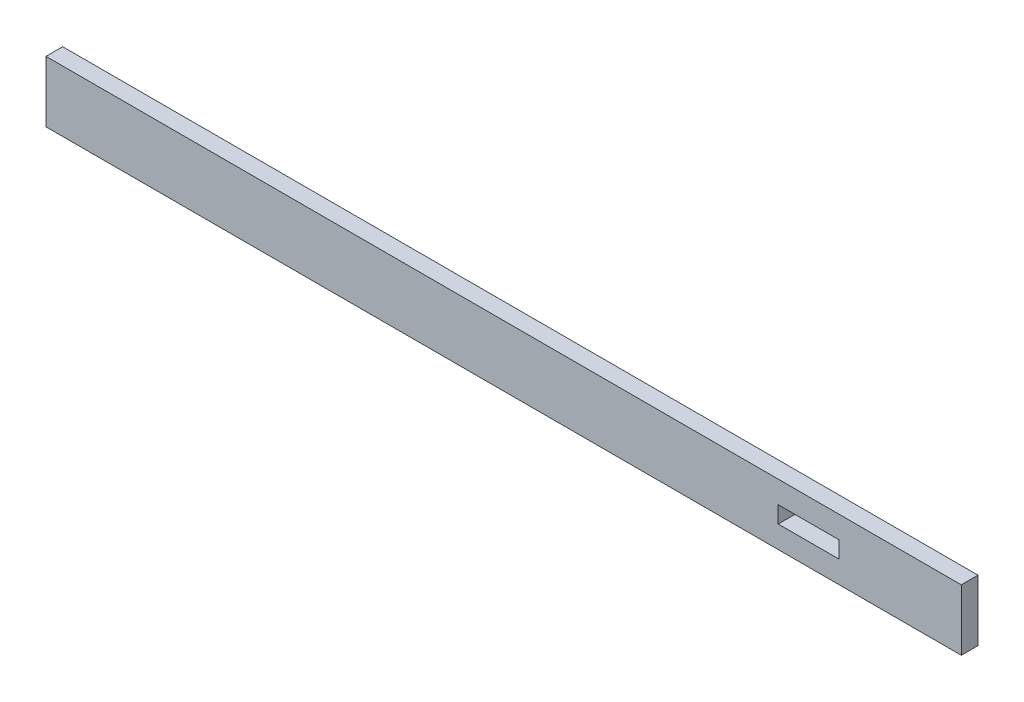
SolidWorks part; units mm, degrees
ref_plane "Front Plane" through (0, 0, 0) normal (1, 0, 0) x (0, 1, 0)
ref_plane "Top Plane" through (0, 0, 0) normal (0, 0, 1) x (0, 1, 0)
ref_plane "Right Plane" through (0, 0, 0) normal (0, 1, 0) x (-1, 0, 0)
sketch "Sketch1" plane through (0, 0, 0) normal (0, 0, 1) x (0, 1, 0)
  line L0 (5, 150) -> (5, 0) construction
  line L1 (0, 0) -> (10, 0)
  line L2 (0, 0) -> (0, 150)
  line L3 (0, 150) -> (10, 150)
  line L4 (10, 0) -> (10, 150)
  line L6 (3.63, 30) -> (6.37, 30)
  line L7 (3.63, 30) -> (3.63, 20)
  line L8 (3.63, 20) -> (6.37, 20)
  line L9 (6.37, 30) -> (6.37, 20)
  line L10 (3.63, 30) -> (6.37, 20) construction
  line L11 (3.63, 20) -> (6.37, 30) construction
  point P7 (5, 25)
  dimension "D1" = 150
  dimension "D2" = 10
  dimension "D3" = 2.74
  dimension "D4" = 10
  dimension "D5" = 20
extrude "Boss-Extrude1" add sketch "Sketch1" along normal blind 2.74
equation "\"cable width\"= .2in"
equation "\"clearance\"= 0.2mm"
equation "\"slot_width\"= \"cable width\" + \"clearance\""
equation "\"base\"= ( \"slot_width\" ) * 3 + 4 * ( 6 )"
equation "\"depth\" = 40mm"
equation "\"thick\"= 3mm"
equation "\"avg_t_wood\"= 2.74mm"
equation "\"ideal_t_wood\"= 3mm"
equation "\"kerf\"= 0.2mm"
equation "\"slot_height\"= \"avg_t_wood\" + \"kerf\""
equation "\"wood_slot_width\"= 10mm + \"kerf\""
equation "\"wood_slot_clearance\"= - .2mm"
equation "\"woodstand_width\"= 10mm"
equation "\"woodstand_length\" = 150mm"
equation "\"D1@Sketch1\"=\"woodstand_length\""
equation "\"D2@Sketch1\"=\"woodstand_width\""
equation "\"D3@Sketch1\"=\"slot_height\"+\"wood_slot_clearance\""
equation "\"D4@Sketch1\"=\"wood_slot_width\"+\"wood_slot_clearance\""
equation "\"D5@Sketch1\"=\"depth\"*0.5"
equation "\"D1@Boss-Extrude1\"=\"avg_t_wood\""
